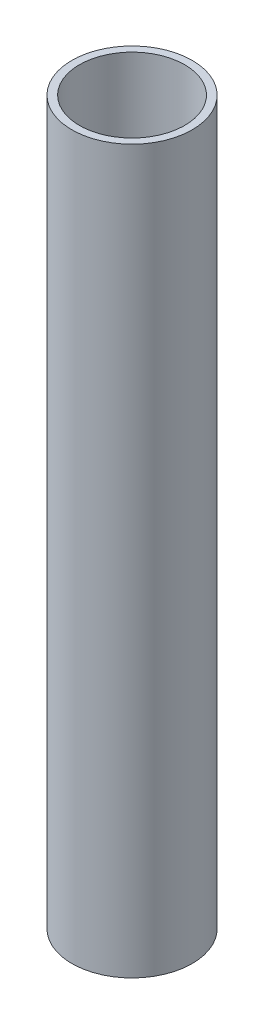
SolidWorks part; units mm, degrees
material "6061-T6 (SS)"
ref_plane "Front Plane" through (0, 0, 0) normal (0, 0, 1) x (1, 0, 0)
ref_plane "Top Plane" through (0, 0, 0) normal (0, 1, 0) x (1, 0, 0)
ref_plane "Right Plane" through (0, 0, 0) normal (1, 0, 0) x (0, 0, -1)
sketch "Sketch1" plane through (0, 0, 0) normal (0, 1, 0) x (1, 0, 0)
  circle A0 centre (0, 0) radius 25.4
  circle A1 centre (0, 0) radius 22.225
  dimension "D1" = 50.8
  dimension "D2" = 3.175
extrude "Boss-Extrude1" add sketch "Sketch1" along normal blind 304.8
